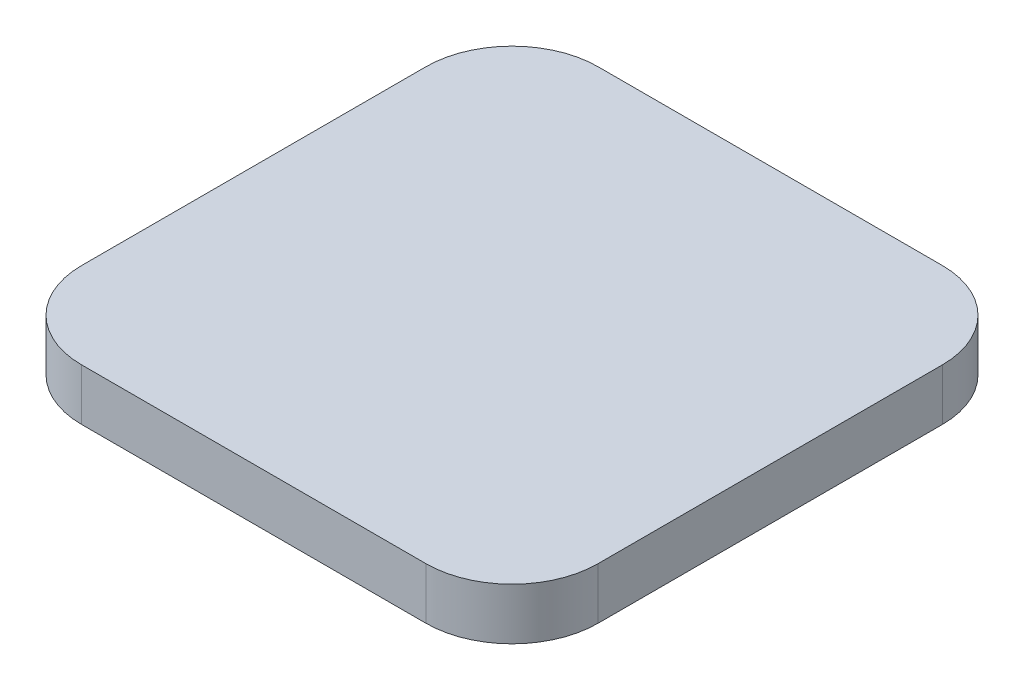
SolidWorks part; units mm, degrees
ref_plane "Front Plane" through (0, 0, 0) normal (0, 0, 1) x (1, 0, 0)
ref_plane "Top Plane" through (0, 0, 0) normal (0, 1, 0) x (1, 0, 0)
ref_plane "Right Plane" through (0, 0, 0) normal (1, 0, 0) x (0, 0, -1)
sketch "Sketch1" plane through (0, 0, 0) normal (0, 1, 0) x (1, 0, 0)
  line L0 (-10, 15) -> (10, 15) construction
  line L1 (-10, -15) -> (10, -15)
  line L2 (-15, -10) -> (-15, 10)
  line L3 (-10, 15) -> (10, 15)
  line L4 (15, -10) -> (15, 10)
  line L5 (-15, -15) -> (15, 15) construction
  line L6 (-15, 15) -> (15, -15) construction
  line L7 (-10, 15) -> (10, 15) construction
  line L8 (15, 10) -> (15, -10) construction
  line L9 (15, 10) -> (15, -10) construction
  line L10 (-15, -10) -> (-15, 10) construction
  line L11 (10, -15) -> (-10, -15) construction
  line L12 (-15, -10) -> (-15, 10) construction
  line L13 (10, -15) -> (-10, -15) construction
  arc A0 (15, 10) -> (10, 15) centre (10, 10) ccw construction
  arc A1 (15, 10) -> (10, 15) centre (10, 10) ccw construction
  arc A2 (10, -15) -> (15, -10) centre (10, -10) ccw construction
  arc A3 (10, -15) -> (15, -10) centre (10, -10) ccw construction
  arc A4 (-15, -10) -> (-10, -15) centre (-10, -10) ccw construction
  arc A5 (-15, -10) -> (-10, -15) centre (-10, -10) ccw construction
  arc A6 (-10, 15) -> (-15, 10) centre (-10, 10) ccw construction
  arc A7 (-10, 15) -> (-15, 10) centre (-10, 10) ccw construction
  arc A8 (-10, -15) -> (-15, -10) centre (-10, -10) cw
  arc A9 (10, -15) -> (15, -10) centre (10, -10) ccw
  arc A10 (-15, 10) -> (-10, 15) centre (-10, 10) cw
  arc A11 (10, 15) -> (15, 10) centre (10, 10) cw
  point P0 (0, 0)
extrude "Boss-Extrude1" add sketch "Sketch1" along normal blind 3
